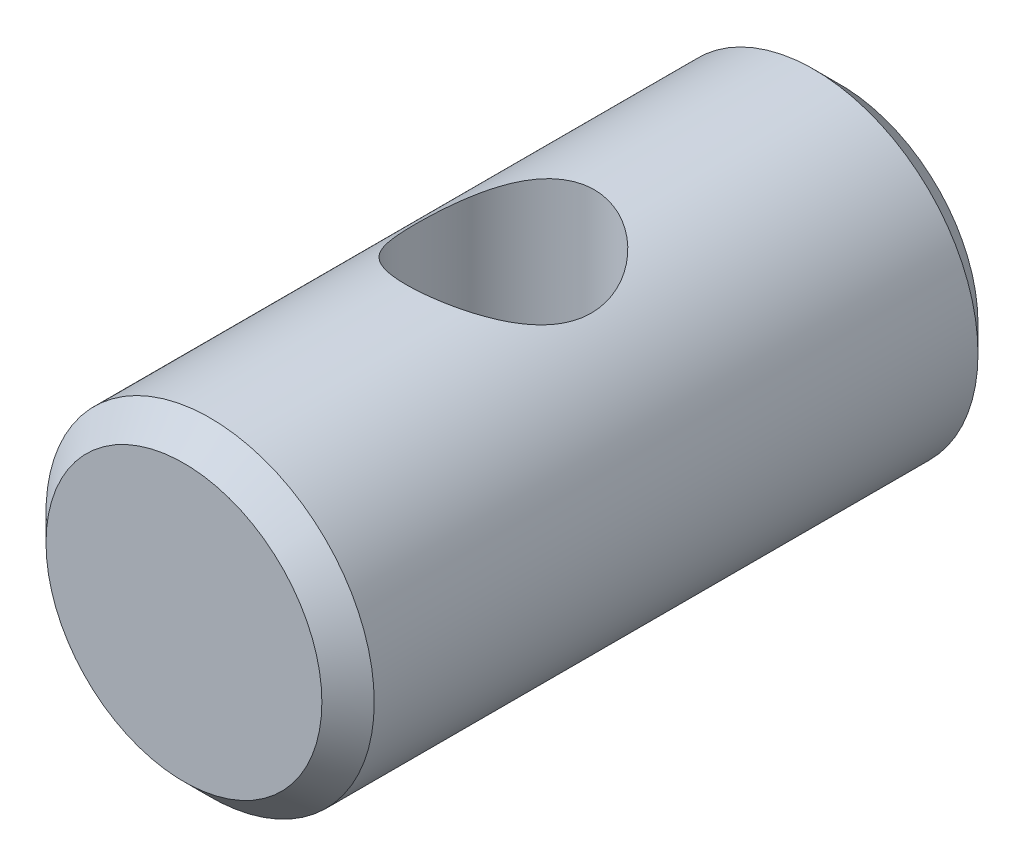
SolidWorks part; units mm, degrees
ref_plane "Front Plane" through (0, 0, 0) normal (0, 0, 1) x (1, 0, 0)
ref_plane "Top Plane" through (0, 0, 0) normal (0, 1, 0) x (1, 0, 0)
ref_plane "Right Plane" through (0, 0, 0) normal (1, 0, 0) x (0, 0, -1)
sketch "Sketch1" plane through (0, 0, 0) normal (0, 0, 1) x (1, 0, 0)
  circle A0 centre (0, 0) radius 4.765
  dimension "D1" = 9.53
extrude "Boss-Extrude1" add sketch "Sketch1" along normal mid plane 19.05
chamfer "Chamfer1" distance 0.76 angle 45 2 edges at (4.765, 0, -9.525) (4.765, 0, 9.525)
sketch "Sketch2" plane through (0, 0, 0) normal (0, 1, 0) x (1, 0, 0)
  circle A1 centre (-0.25, 0) radius 2.555
  dimension "D1" = 5.11
  dimension "D2" = 0.25
extrude "Cut-Extrude1" cut sketch "Sketch2" against normal through all both and the other way through all
